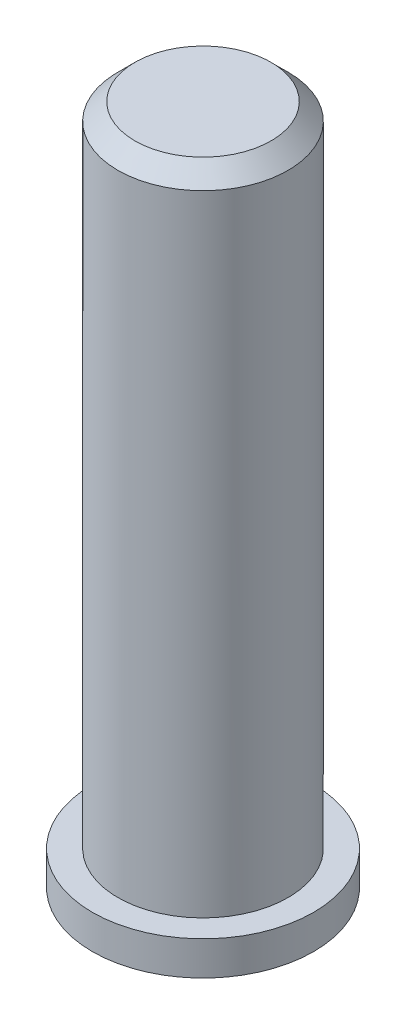
SolidWorks part; units mm, degrees
ref_plane "Спереди" through (0, 0, 0) normal (0, 0, 1) x (1, 0, 0)
ref_plane "Сверху" through (0, 0, 0) normal (0, 1, 0) x (1, 0, 0)
ref_plane "Справа" through (0, 0, 0) normal (1, 0, 0) x (0, 0, -1)
sketch "Эскиз1" plane through (0, 0, 0) normal (0, 1, 0) x (1, 0, 0)
  circle A0 centre (0, 0) radius 2.5
  dimension "D1" = 5
extrude "Вытянуть1" add sketch "Эскиз1" along normal blind 20
chamfer "Фаска1" distance 0.5 angle 45 1 edges at (0, 20, 2.5)
sketch "Эскиз2" plane through (0, 0, 0) normal (0, -1, 0) x (1, 0, 0)
  circle A0 centre (0, 0) radius 3.25
  dimension "D1" = 6.5
extrude "Вытянуть2" add sketch "Эскиз2" against normal blind 1
sketch "Эскиз3" plane through (0, 0, 0) normal (0, -1, 0) x (1, 0, 0)
  circle A0 centre (0, 0) radius 0.375
  dimension "D1" = 0.75
extrude "Вытянуть3" add sketch "Эскиз3" along normal blind 0.8
